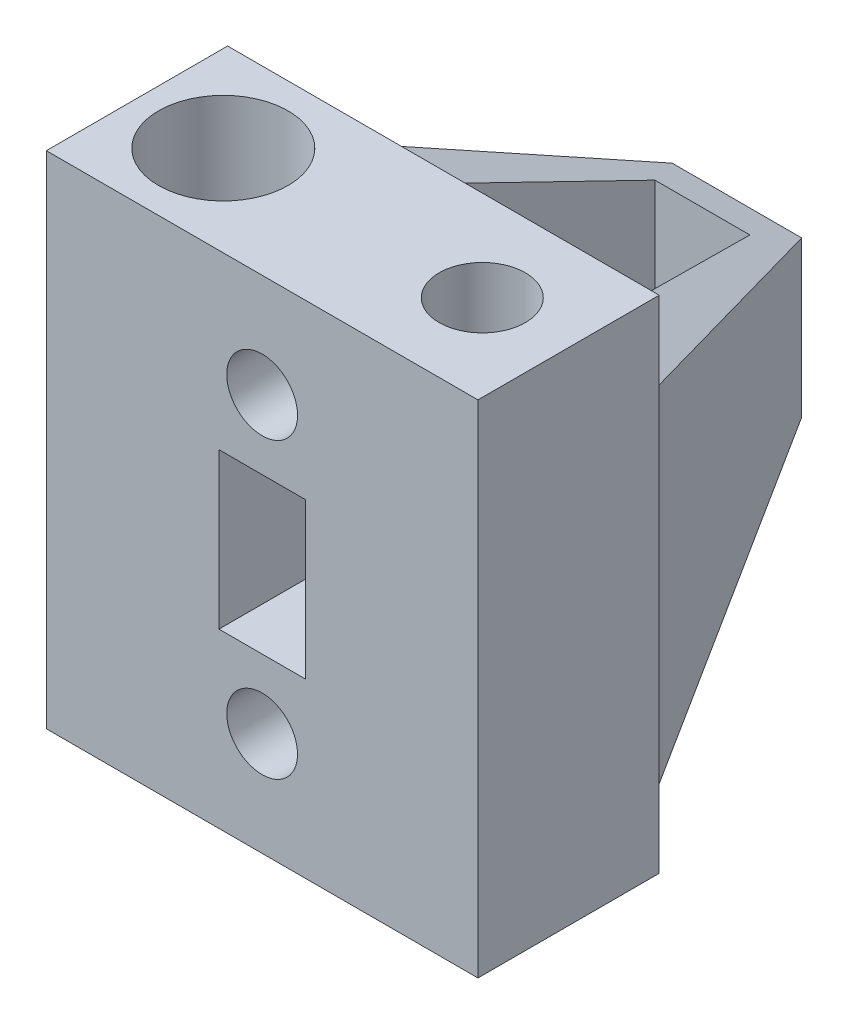
SolidWorks part; units mm, degrees
ref_plane "Front Plane" through (0, 0, 0) normal (0, 0, 1) x (1, 0, 0)
ref_plane "Top Plane" through (0, 0, 0) normal (0, 1, 0) x (1, 0, 0)
ref_plane "Right Plane" through (0, 0, 0) normal (1, 0, 0) x (0, 0, -1)
sketch "Sketch1" plane through (0, 0, 0) normal (0, 1, 0) x (1, 0, 0)
  line L1 (-25, 10.5) -> (25, 10.5)
  line L2 (-25, 10.5) -> (-25, -10.5)
  line L3 (-25, -10.5) -> (25, -10.5)
  line L4 (25, 10.5) -> (25, -10.5)
  line L5 (-25, 10.5) -> (25, -10.5) construction
  line L6 (-25, -10.5) -> (25, 10.5) construction
  point P0 (0, 0)
  dimension "D1" = 21
  dimension "D2" = 50
extrude "Boss-Extrude1" add sketch "Sketch1" along normal blind 58
sketch "Sketch3" plane through (0, 58, 0) normal (0, 1, 0) x (1, 0, 0)
  line L0 (-15, 0) -> (15, 0) construction
  circle A0 centre (-15, 0) radius 7.5
  dimension "D1" = 15
  dimension "D2" = 30
extrude "Cut-Extrude1" cut sketch "Sketch3" against normal blind 24 contours A0
sketch "Sketch4" plane through (0, 58, 0) normal (0, 1, 0) x (1, 0, 0)
  line L0 (-15, 0) -> (15, 0) construction
  circle A0 centre (15, 0) radius 5
  dimension "D1" = 10
extrude "Cut-Extrude2" cut sketch "Sketch4" against normal up to next
sketch "Sketch5" plane through (0, 0, 0) normal (0, -1, 0) x (1, 0, 0)
  circle A1 centre (-15, 0) radius 7.5
  circle A2 centre (-15, 0) radius 7.5
  dimension "D1" = 0
extrude "Cut-Extrude3" cut sketch "Sketch5" against normal blind 24
sketch "Sketch6" plane through (0, 0, 0) normal (0, -1, 0) x (1, 0, 0)
  circle A0 centre (-15, 0) radius 4.5
extrude "Cut-Extrude4" cut sketch "Sketch6" against normal up to next
sketch "Sketch7" plane through (0, 0, 10.5) normal (0, 0, 1) x (1, 0, 0)
  line L0 (0, 58) -> (0, 0) construction
  line L1 (-25, 58) -> (25, 58) construction
  line L2 (-25, 0) -> (25, 0) construction
  line L3 (-25, 29) -> (25, 29) construction
  line L4 (-25, 58) -> (-25, 0) construction
  line L5 (25, 58) -> (25, 0) construction
  circle A1 centre (0, 46) radius 4.1
  circle A2 centre (0, 12) radius 4.1
  point P24 (0, 12)
  dimension "D1" = 8.2
  dimension "D2" = 12
sketch "Sketch8" plane through (0, 0, 10.5) normal (0, 0, 1) x (1, 0, 0)
  line L0 (-25, 29) -> (25, 29) construction
  line L1 (-25, 58) -> (-25, 0) construction
  line L2 (25, 58) -> (25, 0) construction
  line L3 (0, 58) -> (0, 0) construction
  line L4 (-25, 58) -> (25, 58) construction
  line L6 (-5, 20) -> (5, 20)
  line L7 (-5, 20) -> (-5, 38)
  line L8 (-5, 38) -> (5, 38)
  line L9 (5, 20) -> (5, 38)
  line L10 (-5, 20) -> (5, 38) construction
  line L11 (-5, 38) -> (5, 20) construction
  point P11 (0, 29)
  dimension "D1" = 18
  dimension "D2" = 10
extrude "Cut-Extrude5" cut sketch "Sketch8" against normal up to next
sketch "Sketch10" plane through (0, 0, -10.5) normal (0, 0, -1) x (-1, 0, 0)
  line L0 (-25, 29) -> (25, 29) construction
  line L1 (-25, 58) -> (-25, 0) construction
  line L2 (25, 58) -> (25, 0) construction
  line L3 (0, 58) -> (0, 0) construction
  line L4 (-25, 58) -> (25, 58) construction
ref_plane "Plane1" through (0, 29, 0) normal (0, 1, 0) x (0, 0, -1)
sketch "Sketch11" plane through (0, 29, 0) normal (0, 1, 0) x (0, 0, -1)
  line L0 (10.5, 0) -> (63.0219, 0) construction
  line L1 (10.5, -25) -> (10.5, 25) construction
  line L2 (40.5, 5.5) -> (40.5, -5.5)
  line L3 (44.5, 7.5) -> (44.5, -7.5)
  line L4 (44.5, -7.5) -> (10.5, -25)
  line L5 (44.5, 7.5) -> (10.5, 25)
  line L6 (10.5, -25) -> (10.5, -15)
  line L7 (10.5, 25) -> (10.5, 15)
  line L8 (10.5, -15) -> (40.5, -5.5)
  line L9 (10.5, 15) -> (40.5, 5.5)
  point P8 (40.5, 0)
  point P11 (44.5, 0)
  dimension "D1" = 11
  dimension "D2" = 30
  dimension "D3" = 4
  dimension "D4" = 15
  dimension "D5" = 15
extrude "Boss-Extrude3" add sketch "Sketch11" along normal mid plane 40
ref_plane "Plane2" through (0, 0, 0) normal (-1, 0, 0) x (0, 0, 1)
sketch "Sketch12" plane through (0, 0, 0) normal (-1, 0, 0) x (0, 0, 1)
  line L0 (-10.5, 29) -> (-59.7607, 29) construction
  line L1 (-10.5, 58) -> (-10.5, 0) construction
  line L2 (-44.5, 20) -> (-44.5, 38) construction
  line L3 (-44.5, 49) -> (-44.5, 9) construction
  line L4 (-44.5, 38) -> (-10.5, 49)
  line L5 (-44.5, 20) -> (-10.5, 9)
  line L6 (-10.5, 49) -> (-44.5, 49)
  line L7 (-10.5, 9) -> (-44.5, 9)
  line L8 (-44.5, 49) -> (-44.5, 38)
  line L9 (-44.5, 9) -> (-44.5, 20)
  point P9 (-44.5, 29)
  dimension "D1" = 18
extrude "Cut-Extrude6" cut sketch "Sketch12" against normal mid plane 75
sketch "Sketch13" plane through (0, 0, -44.5) normal (0, 0, -1) x (-1, 0, 0)
  line L0 (-25, 29) -> (25, 29) construction
  circle A0 centre (0, 29) radius 2
  dimension "D1" = 4
extrude "Cut-Extrude7" cut sketch "Sketch13" against normal up to next
extrude "Cut-Extrude8" cut sketch "Sketch7" against normal blind 15
